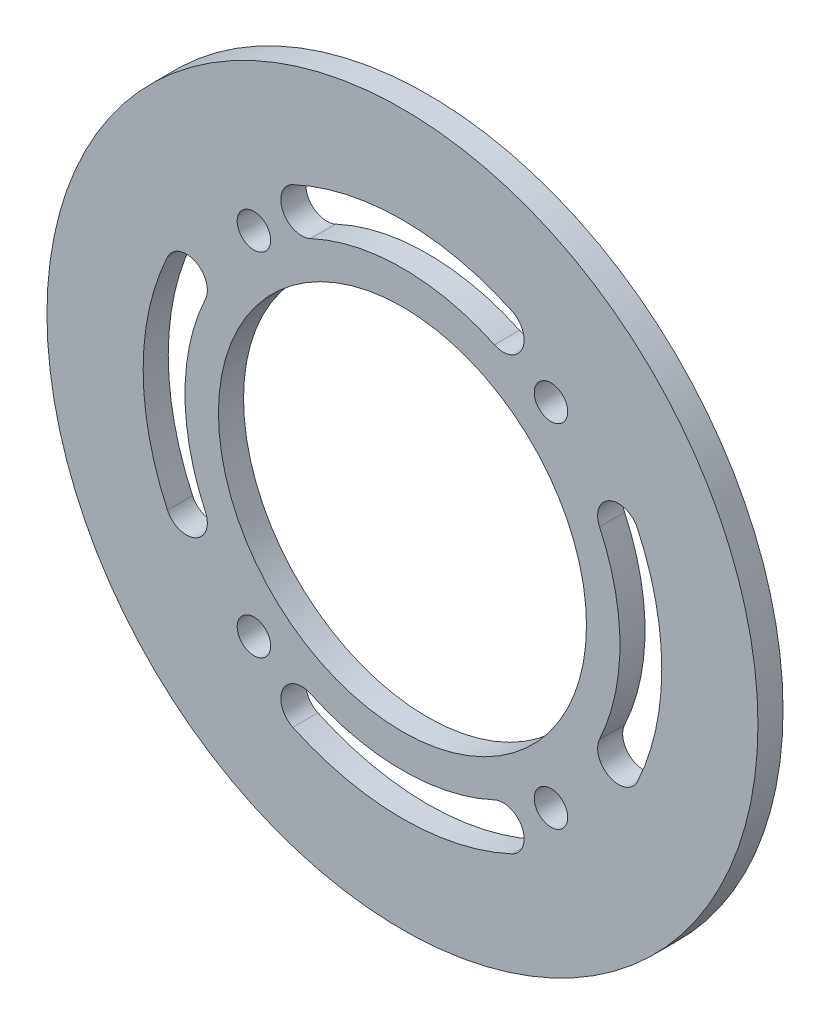
SolidWorks part; units mm, degrees
material "Thornel Mat VMA"
ref_plane "前视基准面" through (0, 0, 0) normal (0, 0, 1) x (1, 0, 0)
ref_plane "上视基准面" through (0, 0, 0) normal (0, 1, 0) x (1, 0, 0)
ref_plane "右视基准面" through (0, 0, 0) normal (1, 0, 0) x (0, 0, -1)
sketch "草图1" plane through (0, 0, 0) normal (0, 0, 1) x (1, 0, 0)
  circle A0 centre (0, 0) radius 22
  circle A1 centre (0, 0) radius 24
  dimension "D1" = 44
  dimension "D2" = 2
extrude "凸台-拉伸1" add sketch "草图1" along normal blind 20
sketch "草图2" plane through (0, 0, 20) normal (0, 0, 1) x (1, 0, 0)
  circle A0 centre (0, 0) radius 22 construction
  circle A1 centre (0, 0) radius 22
  circle A2 centre (0, 0) radius 42.5
  dimension "D1" = 85
extrude "凸台-拉伸2" add sketch "草图2" along normal blind 3
sketch "草图3" plane through (0, 0, 23) normal (0, 0, 1) x (1, 0, 0)
  line L0 (0, 0) -> (42.5, 0) construction
  line L1 (-36.3628, 22) -> (-26.3628, 22)
  line L2 (-40.7707, 12) -> (-26.3628, 12)
  line L3 (-26.3628, 22) -> (-26.3628, 12)
  line L4 (26.3628, 22) -> (26.3628, 12)
  line L5 (0, 42.5) -> (0, 0) construction
  line L6 (26.3628, 12) -> (40.7707, 12)
  line L7 (26.3628, 22) -> (36.3628, 22)
  line L8 (-36.3628, -22) -> (-26.3628, -22)
  line L9 (-26.3628, -22) -> (-26.3628, -12)
  line L10 (-40.7707, -12) -> (-26.3628, -12)
  line L11 (26.3628, -22) -> (26.3628, -12)
  line L12 (26.3628, -22) -> (36.3628, -22)
  line L13 (26.3628, -12) -> (40.7707, -12)
  circle A0 centre (0, 0) radius 42.5 construction
  arc A1 (40.7707, 12) -> (36.3628, 22) centre (0, 0) ccw
  arc A2 (-36.3628, 22) -> (-40.7707, 12) centre (0, 0) ccw
  arc A3 (-36.3628, -22) -> (-40.7707, -12) centre (0, 0) cw
  arc A4 (40.7707, -12) -> (36.3628, -22) centre (0, 0) cw
  dimension "D1" = 22
  dimension "D2" = 10
  dimension "D3" = 10
sketch "草图7" plane through (0, 0, 23) normal (0, 0, 1) x (1, 0, 0)
  line L0 (0, 0) -> (32, 0) construction
  line L2 (-31.225, -7) -> (31.225, -7) construction
  circle A12 centre (0, 0) radius 32 construction
  circle A13 centre (0, -32) radius 2.025
  circle A14 centre (-31.225, -7) radius 1.525 construction
  circle A15 centre (-31.225, 7) radius 1.525 construction
  circle A16 centre (0, 32) radius 2.025
  circle A17 centre (31.225, 7) radius 1.525
  circle A18 centre (31.225, -7) radius 1.525
  dimension "D1" = 4.05
  dimension "D3" = 64
  dimension "D4" = 3.05
  dimension "D2" = 7
sketch "草图10" plane through (0, 0, 23) normal (0, 0, 1) x (1, 0, 0)
  line L0 (0, 0) -> (51.4186, 0) construction
  line L1 (0, 0) -> (0, -51.4186) construction
  line L2 (0, 0) -> (12.0446, -25.8298) construction
  line L3 (0, 0) -> (25.8298, 12.0446) construction
  line L4 (0, 0) -> (-51.4186, 0) construction
  line L5 (0, 0) -> (-25.8298, -12.0446) construction
  line L6 (0, 0) -> (0, 51.4186) construction
  line L7 (0, 0) -> (-12.0446, 25.8298) construction
  arc A0 (25.8298, -12.0446) -> (25.8298, 12.0446) centre (0, 0) ccw construction
  arc A1 (28.0955, -13.1012) -> (28.0955, 13.1012) centre (0, 0) ccw
  arc A2 (23.564, -10.9881) -> (23.564, 10.9881) centre (0, 0) ccw
  arc A3 (23.564, -10.9881) -> (28.0955, -13.1012) centre (25.8298, -12.0446) ccw
  arc A4 (28.0955, 13.1012) -> (23.564, 10.9881) centre (25.8298, 12.0446) ccw
  arc A5 (-12.0446, -25.8298) -> (12.0446, -25.8298) centre (0, 0) ccw construction
  arc A10 (-13.1012, -28.0955) -> (13.1012, -28.0955) centre (0, 0) ccw
  arc A15 (-10.9881, -23.564) -> (10.9881, -23.564) centre (0, 0) ccw
  arc A20 (-10.9881, -23.564) -> (-13.1012, -28.0955) centre (-12.0446, -25.8298) ccw
  arc A21 (13.1012, -28.0955) -> (10.9881, -23.564) centre (12.0446, -25.8298) ccw
  arc A22 (-25.8298, 12.0446) -> (-25.8298, -12.0446) centre (0, 0) ccw construction
  arc A23 (-28.0955, 13.1012) -> (-28.0955, -13.1012) centre (0, 0) ccw
  arc A24 (-23.564, 10.9881) -> (-23.564, -10.9881) centre (0, 0) ccw
  arc A25 (-23.564, 10.9881) -> (-28.0955, 13.1012) centre (-25.8298, 12.0446) ccw
  arc A26 (-28.0955, -13.1012) -> (-23.564, -10.9881) centre (-25.8298, -12.0446) ccw
  arc A27 (12.0446, 25.8298) -> (-12.0446, 25.8298) centre (0, 0) ccw construction
  arc A28 (13.1012, 28.0955) -> (-13.1012, 28.0955) centre (0, 0) ccw
  arc A29 (10.9881, 23.564) -> (-10.9881, 23.564) centre (0, 0) ccw
  arc A30 (10.9881, 23.564) -> (13.1012, 28.0955) centre (12.0446, 25.8298) ccw
  arc A31 (-13.1012, 28.0955) -> (-10.9881, 23.564) centre (-12.0446, 25.8298) ccw
  point P4 (28.5, 0)
  point P17 (0, -28.5)
  point P26 (-28.5, 0)
  point P35 (0, 28.5)
  point P42 (0, 0)
  dimension "D1" = 26
  dimension "D2" = 2.5
  dimension "D3" = 25
  dimension "D4" = 4
extrude "切除-拉伸3" cut sketch "草图10" against normal mid plane 10
sketch "草图12" plane through (0, 0, 0) normal (0, 0, -1) x (-1, 0, 0)
  circle A1 centre (0, 0) radius 24
  circle A2 centre (0, 0) radius 24
  dimension "D1" = 0
extrude "切除-拉伸4" cut sketch "草图12" against normal up to surface (20 mm away) up to face at (26.6366, 0, 20)
sketch "草图13" plane through (0, 0, 0) normal (0, 0, 1) x (1, 0, 0)
  line L0 (0, 0) -> (17.7553, -21) construction
  line L1 (-42.5, 25) -> (42.5, 25) construction
  line L2 (-42.5, 25) -> (-42.5, -25) construction
  line L3 (-42.5, -25) -> (42.5, -25) construction
  line L4 (42.5, 25) -> (42.5, -25) construction
  line L5 (-42.5, 25) -> (42.5, -25) construction
  line L6 (-42.5, -25) -> (42.5, 25) construction
  line L7 (0, 42.5) -> (0, 0) construction
  line L8 (0, 0) -> (42.5, 0) construction
  line L9 (0, 0) -> (42.5, 0) construction
  line L10 (0, 42.5) -> (0, 0) construction
  circle A0 centre (0, 0) radius 42.5 construction
  circle A1 centre (17.7553, -21) radius 2
  circle A2 centre (-17.7553, -21) radius 2
  circle A3 centre (17.7553, 21) radius 2
  circle A4 centre (-17.7553, 21) radius 2
  point P0 (0, 0)
  dimension "D2" = 4
  dimension "D1" = 50
  dimension "D3" = 4
  dimension "D4" = 27.5
extrude "切除-拉伸7" cut sketch "草图13" along normal blind 30
